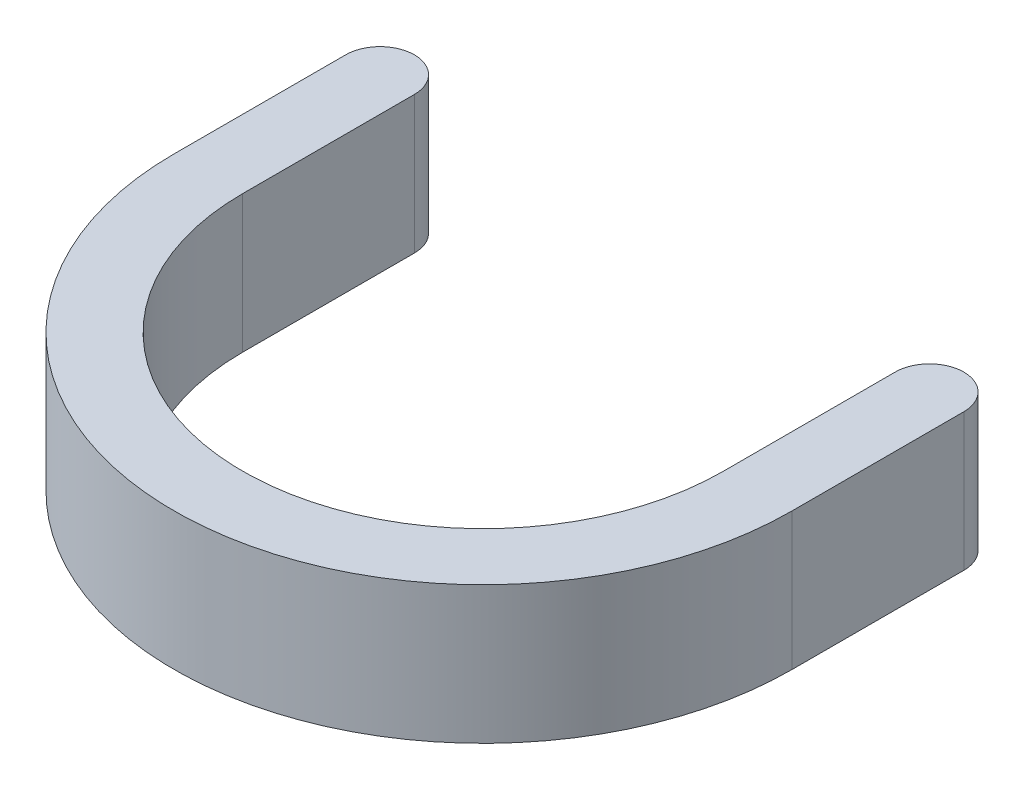
SolidWorks part; units mm, degrees
ref_plane "Front Plane" through (0, 0, 0) normal (0, 0, 1) x (1, 0, 0)
ref_plane "Top Plane" through (0, 0, 0) normal (0, 1, 0) x (1, 0, 0)
ref_plane "Right Plane" through (0, 0, 0) normal (1, 0, 0) x (0, 0, -1)
sketch "Sketch1" plane through (0, 0, 0) normal (0, 1, 0) x (1, 0, 0)
  line L2 (-9, 5) -> (-9, 0)
  line L3 (-7, 0) -> (-7, 5)
  line L6 (9, 0) -> (9, 5)
  line L7 (7, 0) -> (7, 5)
  arc A0 (-7, 0) -> (7, 0) centre (0, 0) ccw
  arc A1 (-9, 0) -> (9, 0) centre (0, 0) ccw
  arc A2 (-7, 5) -> (-9, 5) centre (-8, 5) ccw
  arc A3 (9, 5) -> (7, 5) centre (8, 5) ccw
extrude "Boss-Extrude1" add sketch "Sketch1" along normal blind 4
